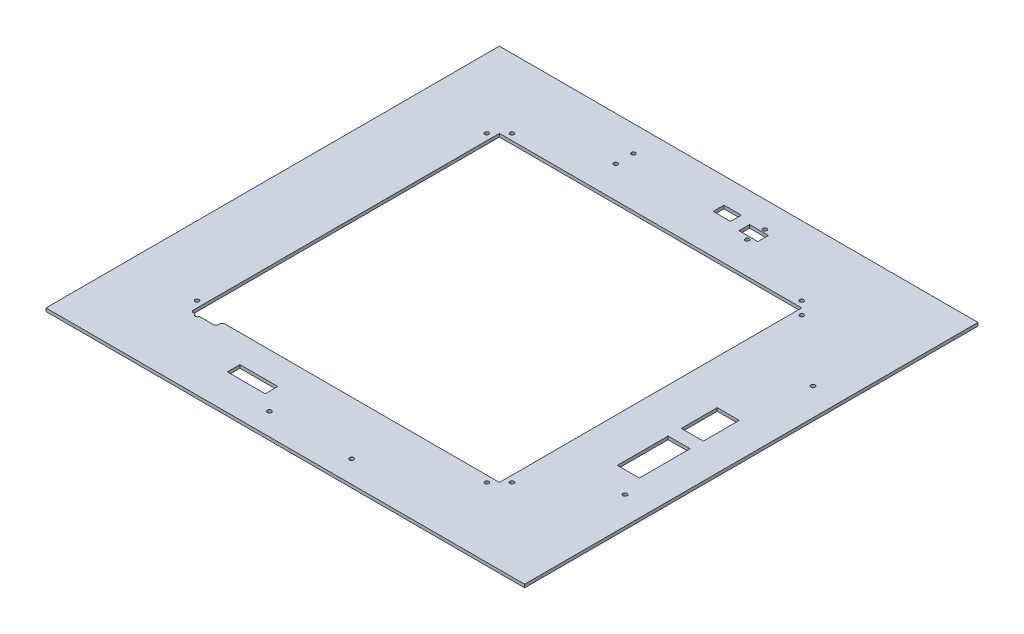
SolidWorks part; units mm, degrees
ref_plane "Front" through (0, 0, 0) normal (0, 0, 1) x (1, 0, 0)
ref_plane "Top" through (0, 0, 0) normal (0, 1, 0) x (1, 0, 0)
ref_plane "Right" through (0, 0, 0) normal (1, 0, 0) x (0, 0, -1)
sketch "Sketch1" plane through (0, 0, 0) normal (0, 1, 0) x (1, 0, 0)
  line L0 (-55, 0) -> (55, 0) construction
  line L1 (-242.5515, 228.6) -> (240.0485, 228.6)
  line L2 (-242.5515, 228.6) -> (-242.5515, -228.6)
  line L3 (-242.5515, -228.6) -> (240.0485, -228.6)
  line L4 (240.0485, 228.6) -> (240.0485, -228.6)
  line L5 (-242.5515, 228.6) -> (240.0485, -228.6) construction
  line L6 (-242.5515, -228.6) -> (240.0485, 228.6) construction
  line L7 (-166.3515, 152.4) -> (138.4485, 152.4)
  line L8 (-166.3515, 152.4) -> (-166.3515, -152.4)
  line L9 (-166.3515, -152.4) -> (138.4485, -152.4)
  line L10 (138.4485, 152.4) -> (138.4485, -152.4)
  line L11 (-166.3515, 152.4) -> (138.4485, -152.4) construction
  line L12 (-166.3515, -152.4) -> (138.4485, 152.4) construction
  line L13 (-160.0015, 146.05) -> (132.0985, 146.05)
  line L14 (-160.0015, 146.05) -> (-160.0015, -146.05)
  line L15 (-160.0015, -146.05) -> (132.0985, -146.05)
  line L16 (132.0985, 146.05) -> (132.0985, -146.05)
  line L17 (-160.0015, 146.05) -> (132.0985, -146.05) construction
  line L18 (-160.0015, -146.05) -> (132.0985, 146.05) construction
  line L19 (-166.3515, -152.4) -> (-140.9515, -152.4)
  line L20 (-166.3515, -152.4) -> (-166.3515, -158.75)
  line L21 (-166.3515, -158.75) -> (-140.9515, -158.75)
  line L22 (-140.9515, -152.4) -> (-140.9515, -158.75)
  line L23 (-242.5515, 0) -> (240.0485, 0) construction
  line L24 (58.4385, 188.214) -> (39.3885, 188.214)
  line L25 (58.4385, 188.214) -> (58.4385, 198.882)
  line L26 (58.4385, 198.882) -> (39.3885, 198.882)
  line L27 (39.3885, 188.214) -> (39.3885, 198.882)
  line L28 (182.9854, -26.8512) -> (205.1825, -26.8512)
  line L29 (182.9854, -26.8512) -> (182.9854, -78.0068)
  line L30 (182.9854, -78.0068) -> (205.1825, -78.0068)
  line L31 (205.1825, -26.8512) -> (205.1825, -78.0068)
  line L32 (182.9854, -13.5376) -> (205.1825, -13.5376)
  line L33 (182.9854, -13.5376) -> (182.9854, 22.6879)
  line L34 (182.9854, 22.6879) -> (205.1825, 22.6879)
  line L35 (205.1825, -13.5376) -> (205.1825, 22.6879)
  line L40 (27.0379, 202.954) -> (9.5991, 202.954)
  line L41 (27.0379, 202.954) -> (27.0379, 192.0704)
  line L42 (27.0379, 192.0704) -> (9.5991, 192.0704)
  line L43 (9.5991, 202.954) -> (9.5991, 192.0704)
  line L44 (-95.2315, -180.3456) -> (-57.1315, -180.3456)
  line L45 (-95.2315, -180.3456) -> (-95.2315, -193.0456)
  line L46 (-95.2315, -193.0456) -> (-57.1315, -193.0456)
  line L47 (-57.1315, -180.3456) -> (-57.1315, -193.0456)
  circle A0 centre (51.3519, 202.311) radius 2
  circle A1 centre (51.3519, 184.531) radius 2
  circle A2 centre (-81.1091, 202.311) radius 2
  circle A3 centre (-81.1091, 184.531) radius 2
  circle A4 centre (212.3904, -99.5798) radius 2.0955
  circle A5 centre (212.3904, 89.828) radius 2.0955
  circle A6 centre (-39.6436, -206.2861) radius 2.1
  circle A7 centre (43.3382, -206.2861) radius 2.1
  circle A8 centre (-172.7335, 146.082) radius 2
  circle A9 centre (-160.0335, 158.782) radius 2
  circle A12 centre (-160.0335, -158.782) radius 2
  circle A13 centre (-172.7335, -146.082) radius 2
  circle A14 centre (132.1305, 158.782) radius 2
  circle A15 centre (144.8305, 146.082) radius 2
  circle A16 centre (144.8305, -146.082) radius 2
  circle A17 centre (132.1305, -158.782) radius 2
  point P0 (-1.2515, 0)
  point P6 (-44.5662, -1.1741)
  point P11 (-84.1987, 3.6789)
  point P21 (-13.9515, 0)
  point P22 (-13.9515, 0)
  point P23 (-1.2515, 0)
  dimension "D15" = 4
  dimension "D16" = 4
  dimension "D17" = 26.289
  dimension "D18" = 17.78
  dimension "D19" = 188.6966
  dimension "D20" = 132.461
  dimension "D22" = 27.6581
  dimension "D23" = 4.191
  dimension "D24" = 129.0202
  dimension "D26" = 4.2
  dimension "D27" = 22.3139
  dimension "D28" = 202.9079
  dimension "D29" = 82.9818
  dimension "D33" = 69.818
  dimension "D34" = 82.518
  dimension "D35" = 4
  dimension "D36" = 69.818
  dimension "D37" = 82.518
  dimension "D38" = 4
  dimension "D39" = 107.918
  dimension "D40" = 69.818
  dimension "D41" = 95.218
  dimension "D42" = 82.518
  dimension "D43" = 95.218
  dimension "D44" = 82.518
  dimension "D45" = 69.818
  dimension "D46" = 107.918
  dimension "D47" = 4
  dimension "D48" = 4
  dimension "D49" = 4
  dimension "D50" = 4
  dimension "D1" = 457.2
  dimension "D2" = 482.6
  dimension "D3" = 304.8
  dimension "D4" = 304.8
  dimension "D5" = 76.2
  dimension "D6" = 292.1
  dimension "D7" = 146.05
  dimension "D8" = 228.6
  dimension "D9" = 25.4
  dimension "D10" = 6.35
  dimension "D11" = 10.668
  dimension "D12" = 181.61
  dimension "D13" = 19.05
  dimension "D14" = 29.718
  dimension "D21" = 17.78
  dimension "D25" = 189.4078
  dimension "D30" = 12.7
  dimension "D31" = 185.42
  dimension "D32" = 38.1
extrude "Boss-Extrude1" add sketch "Sketch1" along normal blind 3.175 contours L4 L1 L2 L3 L7 L10 L9 L8
fillet "Fillet1" radius 2.54 3 edges at (-140.9515, 1.5875, 158.75) (-166.3515, 1.5875, 158.75) (-140.9515, 1.5875, 152.4)
